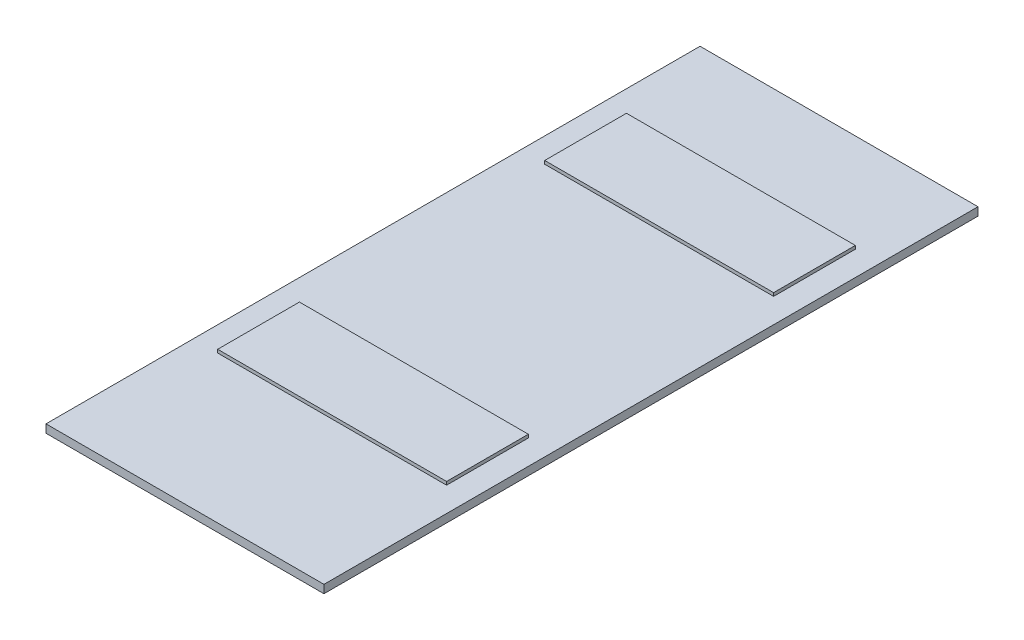
SolidWorks part; units mm, degrees
ref_plane "Front" through (0, 0, 0) normal (0, 0, 1) x (1, 0, 0)
ref_plane "Top" through (0, 0, 0) normal (0, 1, 0) x (1, 0, 0)
ref_plane "Right" through (0, 0, 0) normal (1, 0, 0) x (0, 0, -1)
sketch "Sketch1" plane through (0, 0, 0) normal (0, 1, 0) x (1, 0, 0)
  line L1 (0, 0) -> (85, 0)
  line L2 (0, 0) -> (0, 200)
  line L3 (0, 200) -> (85, 200)
  line L4 (85, 0) -> (85, 200)
  dimension "D1" = 200
  dimension "D2" = 85
extrude "Boss-Extrude1" add sketch "Sketch1" along normal blind 2.5
sketch "Sketch2" plane through (0, 2.5, 0) normal (0, 1, 0) x (1, 0, 0)
  line L0 (7.5, 170) -> (77.5, 170)
  line L1 (7.5, 170) -> (7.5, 145)
  line L2 (77.5, 170) -> (77.5, 145)
  line L3 (77.5, 145) -> (7.5, 145)
  line L4 (7.5, 70) -> (77.5, 70)
  line L5 (7.5, 70) -> (7.5, 45)
  line L6 (77.5, 45) -> (7.5, 45)
  line L7 (77.5, 70) -> (77.5, 45)
  line L8 (0, 200) -> (0, 0) construction
  line L9 (85, 200) -> (0, 200) construction
  dimension "D1" = 25
  dimension "D2" = 70
  dimension "D3" = 75
  dimension "D4" = 7.5
  dimension "D5" = 30
  dimension "D6" = 25
  dimension "D7" = 70
extrude "Boss-Extrude2" add sketch "Sketch2" along normal blind 1
